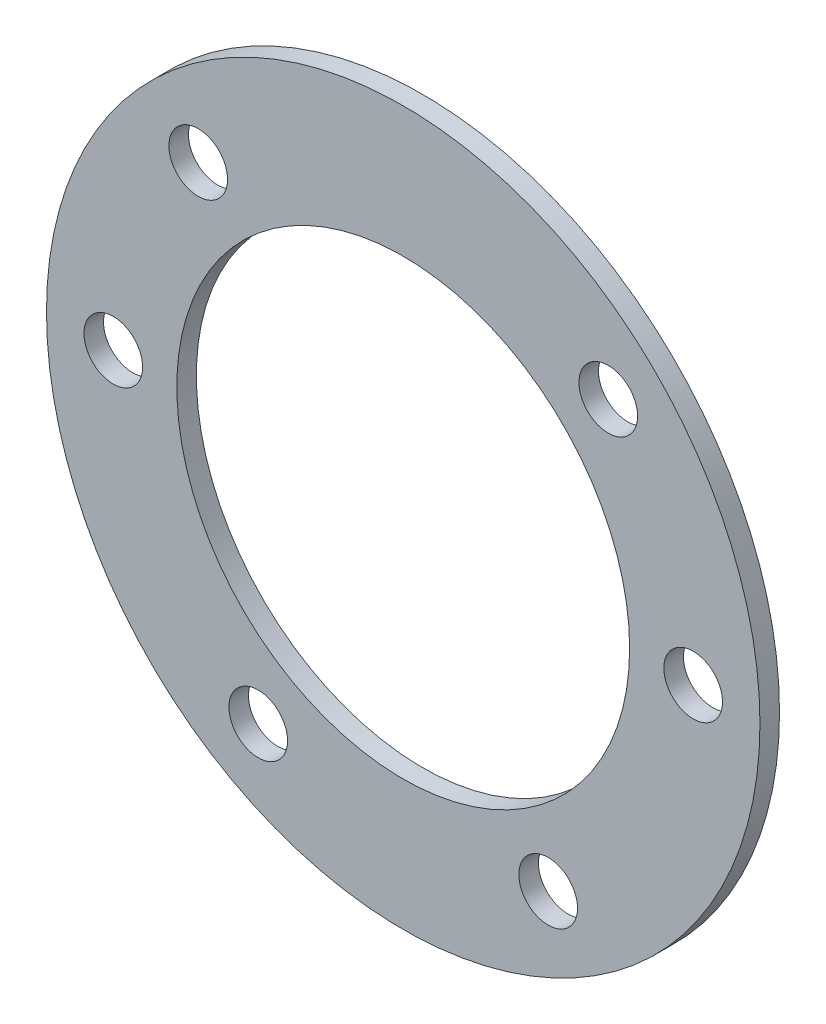
SolidWorks part; units mm, degrees
material "AISI 304"
ref_plane "Спереди" through (0, 0, 0) normal (0, 0, 1) x (1, 0, 0)
ref_plane "Сверху" through (0, 0, 0) normal (0, 1, 0) x (1, 0, 0)
ref_plane "Справа" through (0, 0, 0) normal (1, 0, 0) x (0, 0, -1)
sketch "Эскиз1" plane through (0, 0, 0) normal (0, 0, 1) x (1, 0, 0)
  line L0 (0, 0) -> (-44.5, -77.0763) construction
  line L1 (0, 0) -> (44.5, -77.0763) construction
  line L2 (-89, 0) -> (89, 0) construction
  line L3 (0, 0) -> (-62.9325, 62.9325) construction
  line L4 (0, 0) -> (0, 89) construction
  line L5 (0, 0) -> (62.9325, 62.9325) construction
  circle A0 centre (0, 0) radius 109.5
  circle A1 centre (0, 0) radius 69.5
  circle A2 centre (0, 89) radius 9 construction
  circle A3 centre (0, 0) radius 89 construction
  circle A4 centre (62.9325, 62.9325) radius 9
  circle A5 centre (89, 0) radius 9
  circle A6 centre (-44.5, -77.0763) radius 9
  circle A7 centre (44.5, -77.0763) radius 9
  circle A9 centre (-89, 0) radius 9
  circle A10 centre (-62.9325, 62.9325) radius 9
  circle A11 centre (0, -89) radius 9 [skipped]
  circle A12 centre (-62.9325, -62.9325) radius 9 [skipped]
  circle A13 centre (62.9325, -62.9325) radius 9 [skipped]
  point P23 (0, 0)
  dimension "D1" = 219
  dimension "D2" = 139
  dimension "D3" = 18
  dimension "D4" = 178
  dimension "D6" = 18
  dimension "D7" = 18
  dimension "D14" = 178
  dimension "D8" = 60
  dimension "D9" = 60
  dimension "D10" = 60
  dimension "D11" = 45
  dimension "D12" = 45
  dimension "D13" = 45
  dimension "D5" = 8
extrude "Бобышка-Вытянуть1" add sketch "Эскиз1" along normal blind 6
